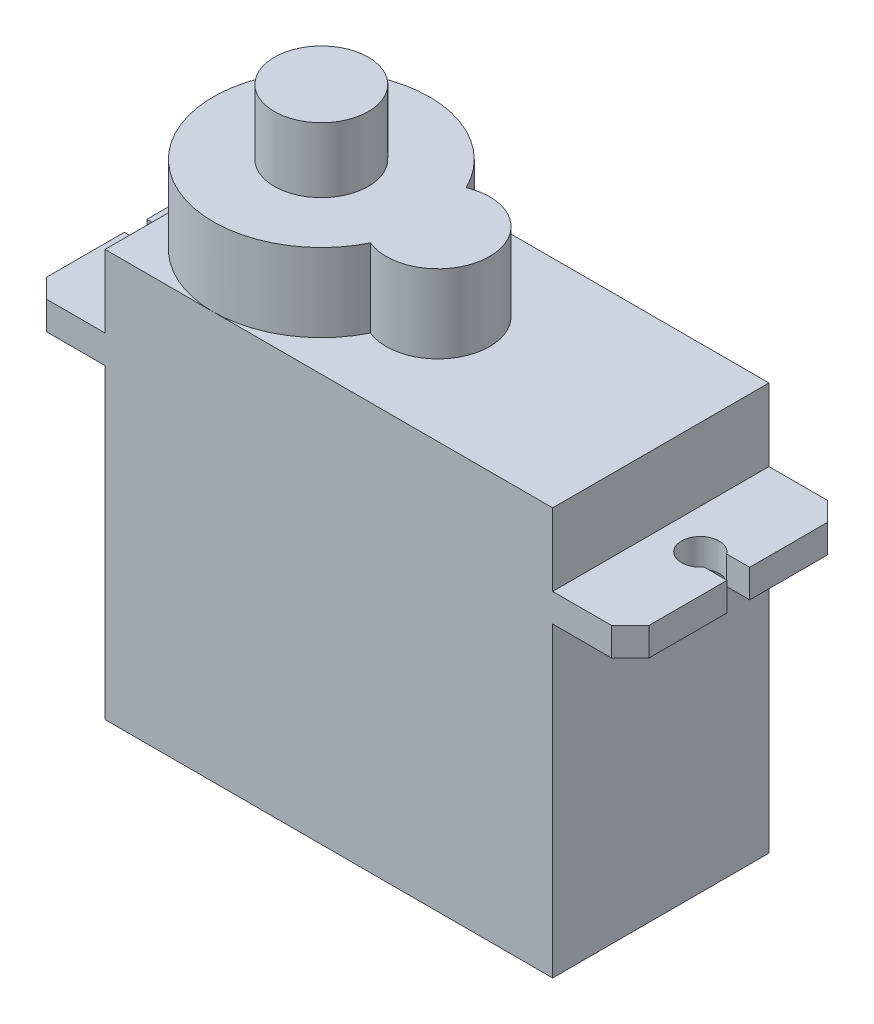
SolidWorks part; units mm, degrees
material "AISI 304"
ref_plane "前视基准面" through (0, 0, 0) normal (0, 0, 1) x (1, 0, 0)
ref_plane "上视基准面" through (0, 0, 0) normal (0, 1, 0) x (1, 0, 0)
ref_plane "右视基准面" through (0, 0, 0) normal (1, 0, 0) x (0, 0, -1)
sketch "草图1" plane through (0, 0, 0) normal (0, 1, 0) x (1, 0, 0)
  line L1 (-11.9, -5.75) -> (11.9, -5.75)
  line L2 (-11.9, -5.75) -> (-11.9, 5.75)
  line L3 (-11.9, 5.75) -> (11.9, 5.75)
  line L4 (11.9, -5.75) -> (11.9, 5.75)
  line L5 (-11.9, -5.75) -> (11.9, 5.75) construction
  line L6 (-11.9, 5.75) -> (11.9, -5.75) construction
  point P0 (0, 0)
  dimension "D1" = 11.5
  dimension "D2" = 23.8
extrude "凸台-拉伸1" add sketch "草图1" along normal blind 21.65
sketch "草图2" plane through (0, 0, 0) normal (0, -1, 0) x (1, 0, 0)
  line L0 (-11.9, 5.75) -> (11.9, 5.75) construction
  line L1 (16.025, -5.75) -> (-16.025, -5.75)
  line L2 (16.025, -5.75) -> (16.025, 5.75)
  line L3 (16.025, 5.75) -> (-16.025, 5.75)
  line L4 (-16.025, -5.75) -> (-16.025, 5.75)
  line L5 (16.025, -5.75) -> (-16.025, 5.75) construction
  line L6 (16.025, 5.75) -> (-16.025, -5.75) construction
  point P0 (0, 0)
  dimension "D1" = 32.05
extrude "凸台-拉伸2" add sketch "草图2" against normal offset from surface (1.5 mm away) 17.8 from offset 16.3 up to face at (0, 0, 0) offset against normal yes
sketch "草图3" plane through (0, 21.65, 0) normal (0, 1, 0) x (1, 0, 0)
  line L0 (11.9, 5.75) -> (-11.9, 5.75) construction
  line L1 (-11.9, 5.75) -> (-11.9, -5.75) construction
  circle A0 centre (-6.15, 0) radius 5.75
  circle A1 centre (0.05, 0) radius 2.75
  dimension "D1" = 5.5
  dimension "D2" = 6.2
extrude "凸台-拉伸3" add sketch "草图3" along normal offset from surface (4.15 mm away) 25.8 contours A1 A0 | A0 A1 | A0 A1 up to face at (0, 0, 0)
sketch "草图4" plane through (0, 25.8, 0) normal (0, 1, 0) x (1, 0, 0)
  circle A0 centre (-6.15, 0) radius 2.5
  dimension "D1" = 5
extrude "凸台-拉伸4" add sketch "草图4" along normal offset from surface (3.45 mm away) 29.25 up to face at (0, 0, 0)
chamfer "倒角1" distance 1 angle 45 4 edges at (16.025, 17.05, -5.75) (16.025, 17.05, 5.75) (-16.025, 17.05, -5.75) (-16.025, 17.05, 5.75)
sketch "草图5" plane through (0, 17.8, 0) normal (0, 1, 0) x (1, 0, 0)
  line L0 (16.025, 0.6) -> (14.8, 0.6)
  line L1 (16.025, -4.75) -> (16.025, 4.75) construction
  line L2 (16.025, 0.6) -> (16.025, -0.6)
  line L3 (16.025, -0.6) -> (14.8, -0.6)
  circle A0 centre (14, 0) radius 1
  line M5 (16.025, -4.75) -> (16.025, 4.75)
  dimension "D1" = 2
  dimension "D2" = 14
  dimension "D3" = 1.2
  dimension "D4" = 0.6
extrude "切除-拉伸1" cut sketch "草图5" against normal up to next contours A0 | A0 L3 L0 M5
mirror "镜向1" about plane through (0, 0, 0) normal (1, 0, 0) of "切除-拉伸1"
